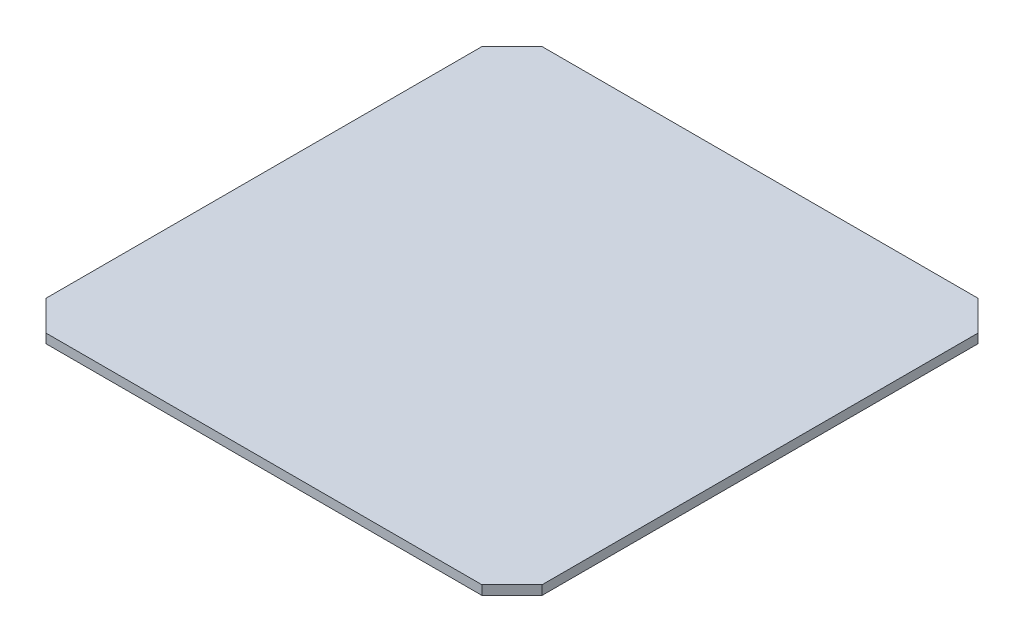
SolidWorks part; units mm, degrees
ref_plane "Front Plane" through (0, 0, 0) normal (0, 0, 1) x (1, 0, 0)
ref_plane "Top Plane" through (0, 0, 0) normal (0, 1, 0) x (1, 0, 0)
ref_plane "Right Plane" through (0, 0, 0) normal (1, 0, 0) x (0, 0, -1)
sketch "Sketch1" plane through (0, 0, 0) normal (0, 1, 0) x (1, 0, 0)
  line L1 (-107, -107) -> (107, -107)
  line L2 (-107, -107) -> (-107, 107)
  line L3 (-107, 107) -> (107, 107)
  line L4 (107, -107) -> (107, 107)
  line L5 (-107, -107) -> (107, 107) construction
  line L6 (-107, 107) -> (107, -107) construction
  point P0 (0, 0)
  dimension "D1" = 214
extrude "Boss-Extrude1" add sketch "Sketch1" along normal blind 4
chamfer "Chamfer1" distance 13 angle 45 4 edges at (-107, 2, -107) (107, 2, -107) (107, 2, 107) (-107, 2, 107)
